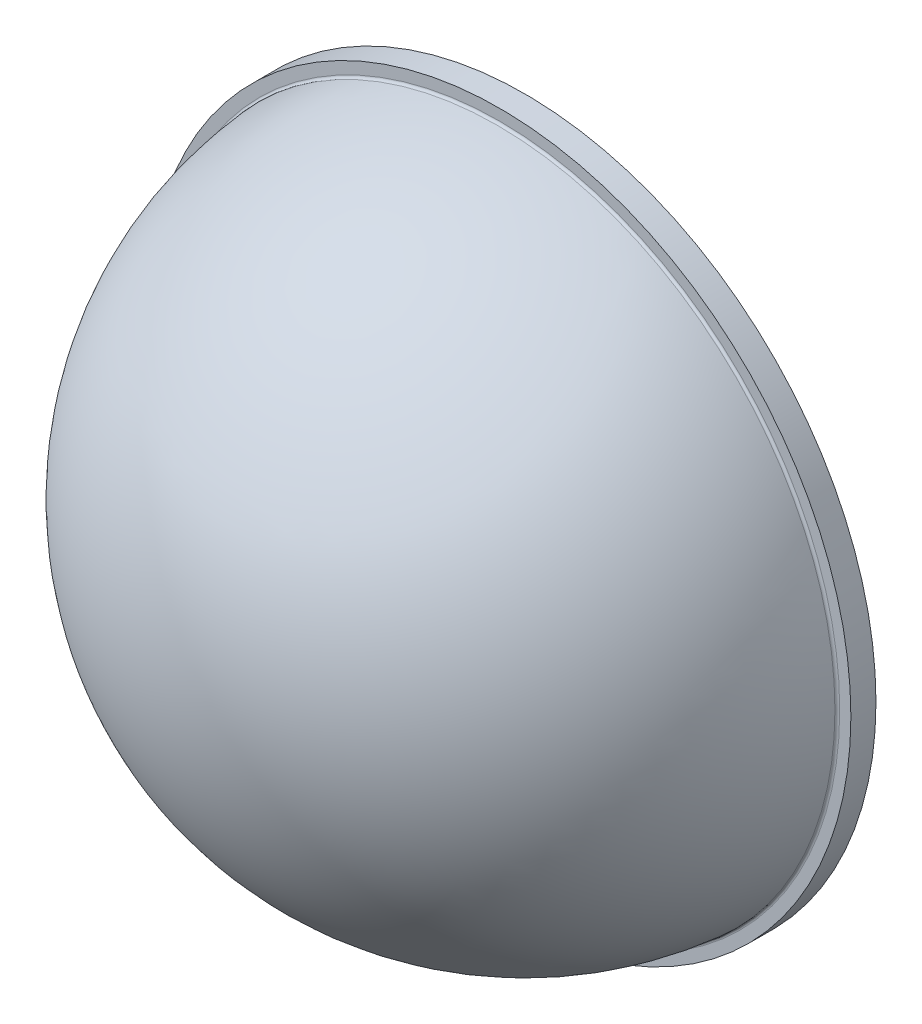
SolidWorks part; units mm, degrees
ref_plane "Ön Düzlem" through (0, 0, 0) normal (0, 0, 1) x (1, 0, 0)
ref_plane "Üst Düzlem" through (0, 0, 0) normal (0, 1, 0) x (1, 0, 0)
ref_plane "Sağ Düzlem" through (0, 0, 0) normal (1, 0, 0) x (0, 0, -1)
sketch "Sketch1" plane through (0, 0, 0) normal (0, 0, 1) x (1, 0, 0)
  circle A0 centre (0, 0) radius 70
  circle A1 centre (0, 0) radius 65
  dimension "D1" = 140
  dimension "D2" = 130
extrude "Boss-Extrude1" add sketch "Sketch1" along normal blind 5
sketch "Sketch2" plane through (0, 0, 0) normal (0, 0, 1) x (1, 0, 0)
  line L0 (0, 67.5) -> (0, 65)
  line L1 (0, -65) -> (0, -67.5)
  arc A0 (0, -65) -> (0, 65) centre (0, 0) ccw
  arc A1 (0, -67.5) -> (0, 67.5) centre (0, 0) ccw
  dimension "D1" = 130
  dimension "D2" = 135
revolve "Revolve1" add sketch "Sketch2" angle 180 about L0
fillet "Fillet1" radius 0.5 2 edges at (67.3146, 0, 5) (-65, 0, 0)
